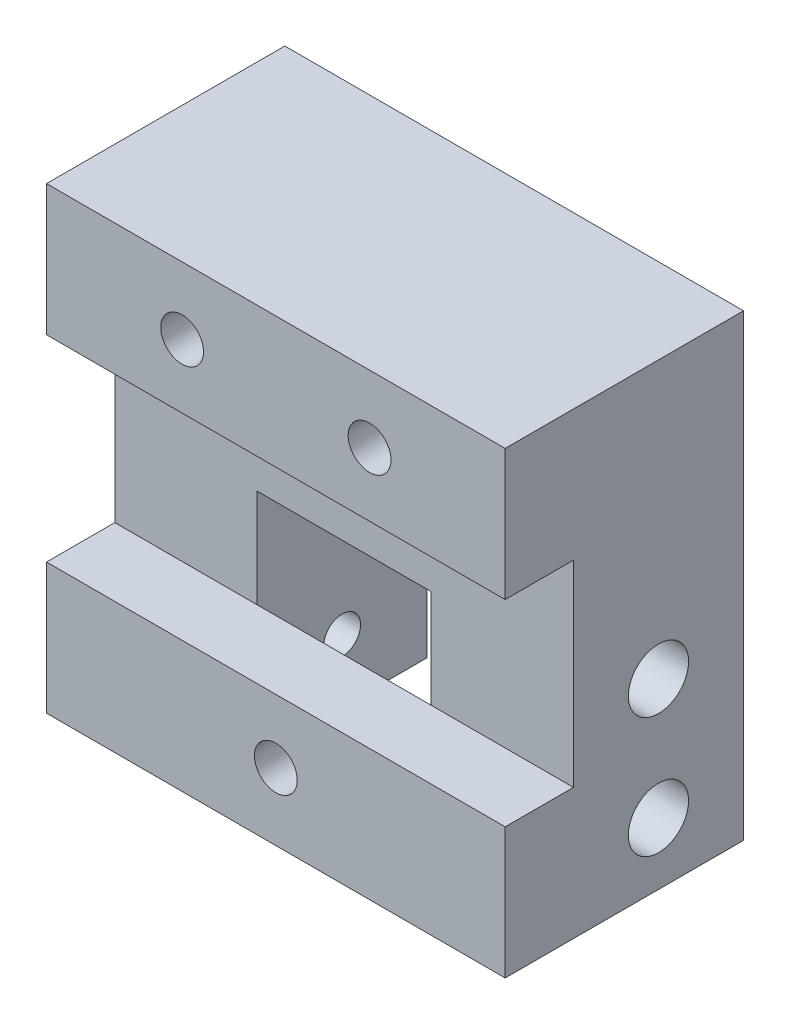
SolidWorks part; units mm, degrees
ref_plane "Front Plane" through (0, 0, 0) normal (0, 0, 1) x (1, 0, 0)
ref_plane "Top Plane" through (0, 0, 0) normal (0, 1, 0) x (1, 0, 0)
ref_plane "Right Plane" through (0, 0, 0) normal (1, 0, 0) x (0, 0, -1)
sketch "Sketch1" plane through (0, 0, 0) normal (0, 0, 1) x (1, 0, 0)
  line L1 (-34.26, 34.26) -> (34.26, 34.26)
  line L2 (-34.26, 34.26) -> (-34.26, -34.26)
  line L3 (-34.26, -34.26) -> (34.26, -34.26)
  line L4 (34.26, 34.26) -> (34.26, -34.26)
  point P4 (0, 34.26)
  point P6 (-34.26, 0)
  dimension "D1" = 68.52
extrude "Boss-Extrude1" add sketch "Sketch1" along normal blind 35.6
sketch "Sketch2" plane through (0, 0, 35.6) normal (0, 0, 1) x (1, 0, 0)
  line L0 (-34.26, 34.26) -> (-34.26, -34.26) construction
  line L1 (-34.26, -14.7) -> (34.26, -14.7)
  line L2 (-34.26, -14.7) -> (-34.26, 14.7)
  line L3 (-34.26, 14.7) -> (34.26, 14.7)
  line L4 (34.26, -14.7) -> (34.26, 14.7)
  line L5 (34.26, -34.26) -> (34.26, 34.26) construction
  point P8 (34.26, 0)
  dimension "D1" = 29.4
extrude "Cut-Extrude1" cut sketch "Sketch2" against normal blind 10.2
sketch "Sketch3" plane through (0, 0, 35.6) normal (0, 0, 1) x (1, 0, 0)
  line L0 (-14, 24.2141) -> (14, 24.2141) construction
  line L1 (0, -24.2141) -> (0, 24.2141) construction
  circle A0 centre (-14, 24.2141) radius 3.2
  circle A1 centre (14, 24.2141) radius 3.2
  circle A2 centre (0, -24.2141) radius 3.2
  point P6 (0, 24.2141)
  point P8 (0, 0)
  dimension "D2" = 6.4
  dimension "D3" = 6.4
  dimension "D4" = 6.4
  dimension "D1" = 48.4283
  dimension "D5" = 28
extrude "Cut-Extrude2" cut sketch "Sketch3" against normal blind 10.2
sketch "Sketch4" plane through (0, 0, 0) normal (0, 0, -1) x (-1, 0, 0)
  line L0 (34.26, -34.26) -> (-34.26, -34.26) construction
  line L1 (-13, -34.26) -> (13, -34.26)
  line L2 (-13, -34.26) -> (-13, 0)
  line L3 (-13, 0) -> (13, 0)
  line L4 (13, -34.26) -> (13, 0)
  point P6 (0, 0)
  dimension "D1" = 26
extrude "Cut-Extrude3" cut sketch "Sketch4" against normal blind 25.4
sketch "Sketch6" plane through (34.26, 0, 0) normal (1, 0, 0) x (0, 0, -1)
  line L0 (-25.4, 0) -> (0, 0) construction
  line L1 (-25.4, 0) -> (0, 0) construction
  circle A0 centre (-12.7, -7) radius 2.75
  circle A1 centre (-12.7, -25) radius 2.75
  point P7 (-12.7, 0)
  dimension "D2" = 5.5
  dimension "D3" = 5.5
  dimension "D1" = 7
  dimension "D4" = 25
extrude "Cut-Extrude4" cut sketch "Sketch6" against normal through all both and the other way through all
sketch "Sketch7" plane through (34.26, 0, 0) normal (1, 0, 0) x (0, 0, -1)
  circle A0 centre (-12.7, -7) radius 2.75 construction
  circle A1 centre (-12.7, -7) radius 2.75 construction
  circle A2 centre (-12.7, -7) radius 4.5
  circle A3 centre (-12.7, -25) radius 4.5
  dimension "D1" = 9
  dimension "D2" = 9
extrude "Cut-Extrude5" cut sketch "Sketch7" against normal offset from surface (13.26 mm away) 8 up to face at (13, -4.25, 12.7)
sketch "Sketch8" plane through (-34.26, 0, 0) normal (-1, 0, 0) x (0, 0, 1)
  circle A0 centre (12.7, -7) radius 4.5
  circle A1 centre (12.7, -25) radius 4.5
  dimension "D1" = 9
  dimension "D2" = 9
extrude "Cut-Extrude6" cut sketch "Sketch8" against normal offset from surface (13.26 mm away) 8 up to face at (-13, -9.75, 12.7)
